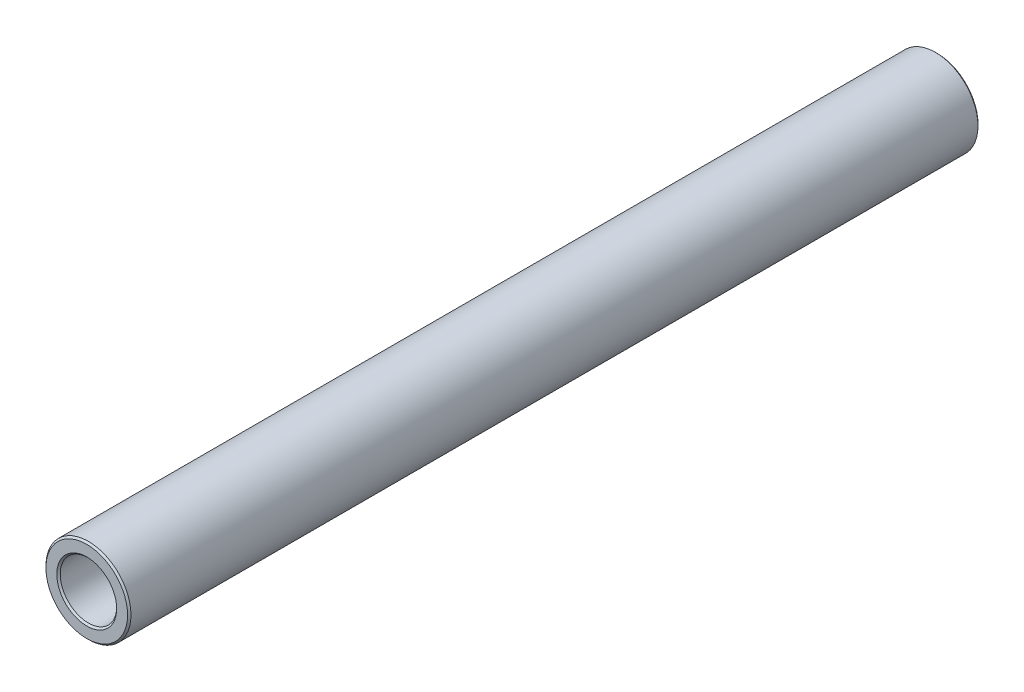
SolidWorks part; units mm, degrees
material "6061 Alloy"
ref_plane "Front Plane" through (0, 0, 0) normal (0, 0, 1) x (1, 0, 0)
ref_plane "Top Plane" through (0, 0, 0) normal (0, 1, 0) x (1, 0, 0)
ref_plane "Right Plane" through (0, 0, 0) normal (1, 0, 0) x (0, 0, -1)
sketch "Sketch1" plane through (0, 0, 0) normal (0, 0, 1) x (1, 0, 0)
  circle A0 centre (0, 0) radius 2.1082
  circle A1 centre (0, 0) radius 3.175
  dimension "D1" = 6.35
  dimension "D2" = 4.2164
extrude "Boss-Extrude1" add sketch "Sketch1" along normal blind 63.5
chamfer "Chamfer1" distance 0.127 angle 45 4 edges at (2.1082, 0, 0) (3.175, 0, 0) (2.1082, 0, 63.5) (3.175, 0, 63.5)
